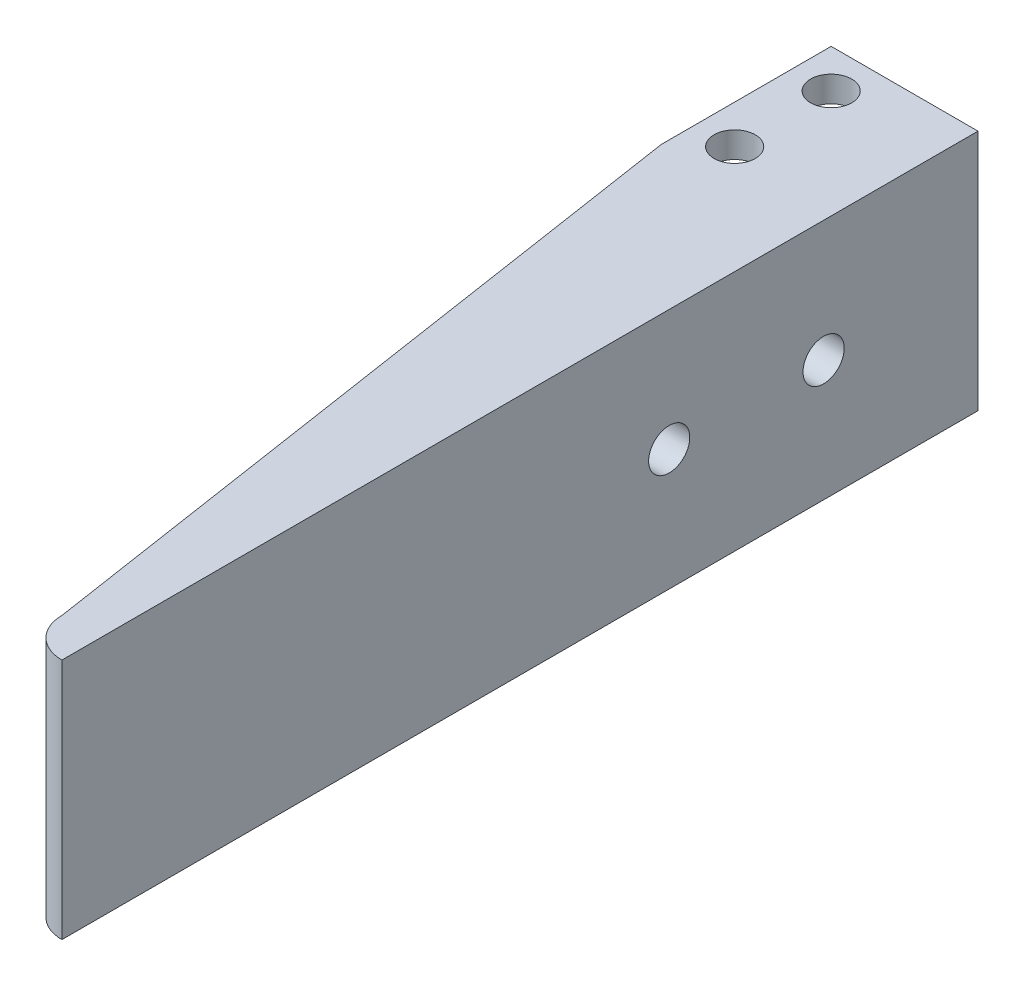
SolidWorks part; units mm, degrees
ref_plane "Front Plane" through (0, 0, 0) normal (0, 0, 1) x (1, 0, 0)
ref_plane "Top Plane" through (0, 0, 0) normal (0, 1, 0) x (1, 0, 0)
ref_plane "Right Plane" through (0, 0, 0) normal (1, 0, 0) x (0, 0, -1)
sketch "Sketch1" plane through (0, 0, 0) normal (0, 1, 0) x (1, 0, 0)
  line L0 (-5.7062, 0) -> (5.7062, 0)
  line L1 (-5.7062, 0) -> (-5.7062, -13.2)
  line L2 (-5.7062, -13.2) -> (2.7063, -68.2)
  line L5 (5.7062, 0) -> (5.7063, -68.2) construction
  line L6 (5.7063, -71.2) -> (5.7062, 0)
  arc A0 (2.7063, -68.2) -> (5.7063, -71.2) centre (5.7063, -68.2) ccw
  circle A1 centre (-2.7062, -3) radius 1.6
  circle A2 centre (-2.7062, -10.5) radius 1.6
  point P3 (0, 0)
  dimension "D1" = 3
  dimension "D8" = 3.2
  dimension "D2" = 11.4125
  dimension "D3" = 13.2
  dimension "D4" = 55
  dimension "D5" = 3
  dimension "D6" = 7.5
  dimension "D7" = 3
extrude "Boss-Extrude1" add sketch "Sketch1" along normal blind 2
sketch "Sketch2" plane through (0, 0, 0) normal (0, -1, 0) x (1, 0, 0)
  line L0 (5.7062, 0) -> (-5.7062, 0) construction
  line L1 (5.7063, 71.2) -> (5.7063, 0)
  line L8 (5.7063, 0) -> (2.7063, 0)
  line L9 (2.7063, 68.2) -> (2.7063, 0)
  line L10 (5.7063, 71.2) -> (5.7062, 0) construction
  arc A2 (5.7063, 71.2) -> (2.7063, 68.2) centre (5.7063, 68.2) ccw
extrude "Boss-Extrude2" add sketch "Sketch2" along normal blind 7.41
ref_plane "Plane1" through (0, -7.41, 0) normal (0, -1, 0) x (-1, 0, 0)
mirror "Mirror6" about plane through (0, -7.41, 0) normal (0, -1, 0) of "Boss-Extrude1", "Boss-Extrude2"
mirror "Mirror7" about plane through (0, -7.41, 0) normal (0, -1, 0) of "Boss-Extrude1"
sketch "Sketch3" plane through (2.7063, 0, 0) normal (-1, 0, 0) x (0, 0, 1)
  line L0 (71.2, -7.41) -> (0, -7.41) construction
  line L1 (71.2, 2) -> (71.2, -16.82) construction
  line L2 (0, 2) -> (0, -16.82) construction
  circle A0 centre (24, -7.41) radius 1.6
  circle A1 centre (12, -7.41) radius 1.6
  dimension "D1" = 3.2
  dimension "D2" = 12
  dimension "D3" = 12
extrude "Cut-Extrude1" cut sketch "Sketch3" against normal through all both and the other way through all
